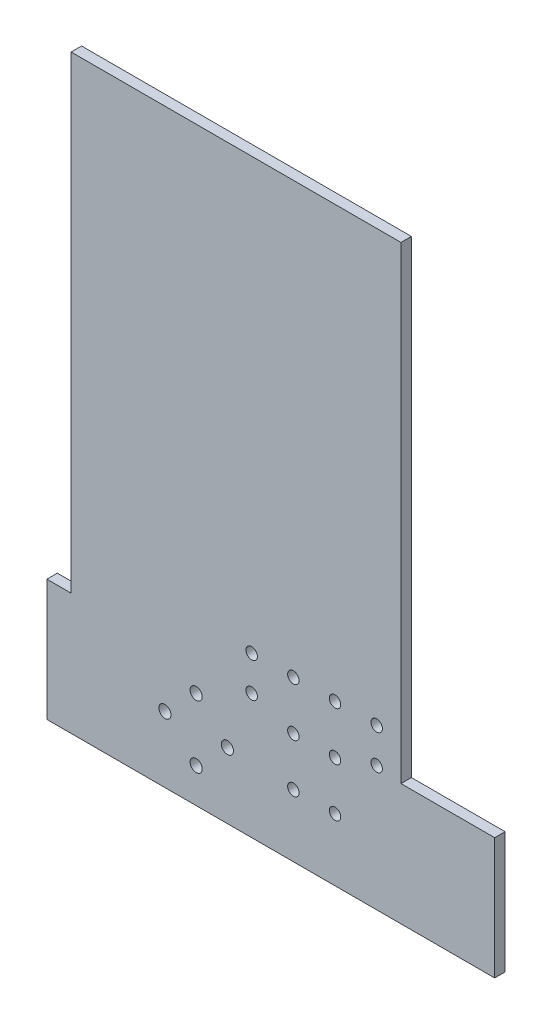
SolidWorks part; units mm, degrees
ref_plane "前视基准面" through (0, 0, 0) normal (0, 0, 1) x (1, 0, 0)
ref_plane "上视基准面" through (0, 0, 0) normal (0, 1, 0) x (1, 0, 0)
ref_plane "右视基准面" through (0, 0, 0) normal (1, 0, 0) x (0, 0, -1)
other "Configuration Table"
sketch "草图1" plane through (0, 0, 0) normal (0, 0, 1) x (1, 0, 0)
  line L0 (19, -7) -> (19, -16) construction
  line L1 (0, 0) -> (105, 0)
  line L2 (0, 0) -> (0, -35)
  line L3 (0, -35) -> (105, -35)
  line L4 (105, 0) -> (105, -35)
  line L5 (19, -25) -> (28, -16) construction
  line L6 (28, -16) -> (19, -7) construction
  line L7 (19, -7) -> (10, -16) construction
  line L8 (10, -16) -> (19, -25) construction
  circle A0 centre (19, -16) radius 6.364 construction
  circle A1 centre (19, -7) radius 1.75
  circle A2 centre (10, -16) radius 1.75
  circle A3 centre (19, -25) radius 1.75
  circle A4 centre (28, -16) radius 1.75
  dimension "D2" = 3.5
  dimension "D1" = 9
  dimension "D3" = 35
  dimension "D4" = 105
  dimension "D5" = 19
  dimension "D6" = 16
extrude "凸台-拉伸1" add sketch "草图1" along normal blind 3
sketch "草图2" plane through (0, 0, 3) normal (0, 0, 1) x (1, 0, 0)
  circle A1 centre (47, -3) radius 1.65
  circle A2 centre (47, -3) radius 1.65
  circle A3 centre (59, -3) radius 1.65
  circle A4 centre (59, -3) radius 1.65
  circle A5 centre (47, 11) radius 1.65
  circle A6 centre (47, 11) radius 1.65
  circle A7 centre (59, 11) radius 1.65
  circle A8 centre (59, 11) radius 1.65
  circle A14 centre (71, 11) radius 1.65 construction
  circle A15 centre (71, 11) radius 1.65
  circle A16 centre (35, 11) radius 1.65 construction
  circle A17 centre (35, 11) radius 1.65
  circle A18 centre (35, 1) radius 1.65 construction
  circle A19 centre (35, 1) radius 1.65
  circle A20 centre (71, 1) radius 1.65 construction
  circle A21 centre (71, 1) radius 1.65
  circle A22 centre (47, -17) radius 1.65 construction
  circle A23 centre (47, -17) radius 1.65
  circle A24 centre (59, -17) radius 1.65 construction
  circle A25 centre (59, -17) radius 1.65
  dimension "D1" = 0
  dimension "D2" = 0
  dimension "D3" = 0
  dimension "D4" = 0
sketch "草图3" plane through (0, 0, 3) normal (0, 0, 1) x (1, 0, 0)
  line L0 (0, 0) -> (-24, 0)
  line L1 (-24, 0) -> (-24, -35)
  line L2 (-24, -35) -> (0, -35)
  line L3 (0, -35) -> (0, 0)
  dimension "D1" = 24
extrude "凸台-拉伸2" add sketch "草图3" against normal blind 3
sketch "草图4" plane through (0, 0, 3) normal (0, 0, 1) x (1, 0, 0)
  line L0 (-17, 0) -> (-17, 135)
  line L1 (105, 0) -> (-24, 0) construction
  line L2 (-17, 135) -> (78, 135)
  line L3 (78, 135) -> (78, 0)
  line L4 (78, 0) -> (-17, 0)
  line L5 (-24, 0) -> (-24, -35) construction
  dimension "D1" = 135
  dimension "D2" = 7
  dimension "D3" = 95
extrude "凸台-拉伸3" add sketch "草图4" against normal blind 3
extrude "切除-拉伸1" cut sketch "草图2" against normal through all
